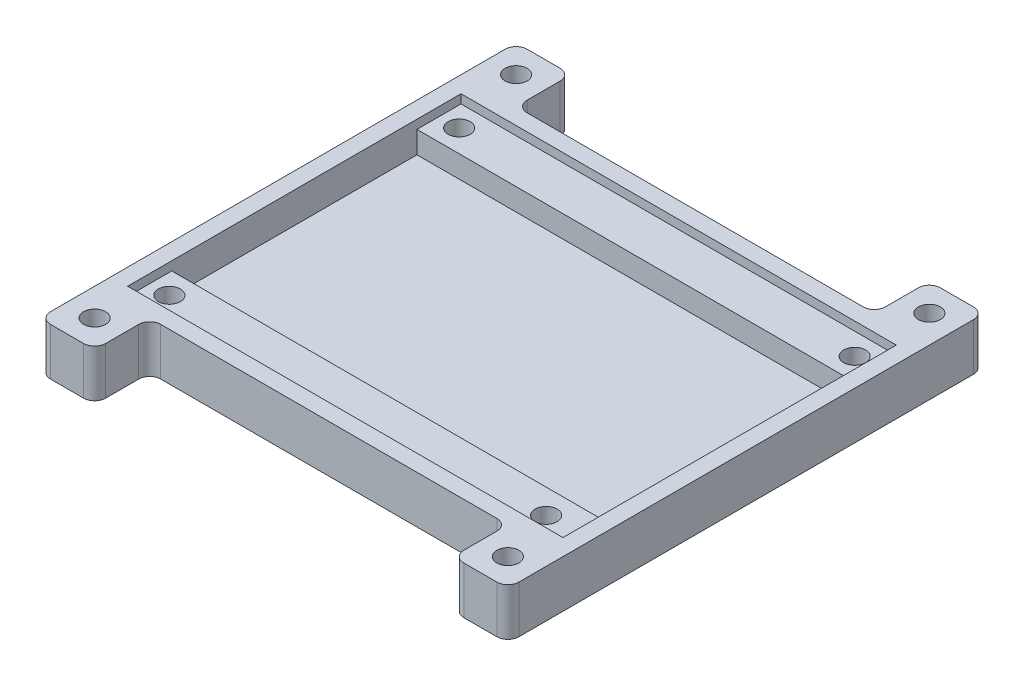
SolidWorks part; units mm, degrees
ref_plane "Front Plane" through (0, 0, 0) normal (0, 0, 1) x (1, 0, 0)
ref_plane "Top Plane" through (0, 0, 0) normal (0, 1, 0) x (1, 0, 0)
ref_plane "Right Plane" through (0, 0, 0) normal (1, 0, 0) x (0, 0, -1)
sketch "Sketch2" plane through (0, 0, 0) normal (0, 1, 0) x (1, 0, 0)
  line L1 (-42.5, -33.25) -> (42.5, -33.25)
  line L2 (-42.5, -33.25) -> (-42.5, 33.25)
  line L3 (-42.5, 33.25) -> (42.5, 33.25)
  line L4 (42.5, -33.25) -> (42.5, 33.25)
  line L5 (-42.5, -33.25) -> (42.5, 33.25) construction
  line L6 (-42.5, 33.25) -> (42.5, -33.25) construction
  point P0 (0, 0)
  dimension "D1" = 66.5
  dimension "D2" = 85
extrude "Boss-Extrude2" add sketch "Sketch2" along normal blind 3
sketch "Sketch3" plane through (0, 3, 0) normal (0, 1, 0) x (1, 0, 0)
  line L0 (-39.5, 30.25) -> (-39.5, -30.25)
  line L1 (-39.5, -30.25) -> (39.5, -30.25)
  line L2 (39.5, -30.25) -> (39.5, 30.25)
  line L3 (39.5, 30.25) -> (-39.5, 30.25)
  line L4 (42.5, -33.25) -> (42.5, 33.25)
  line L5 (42.5, 33.25) -> (-42.5, 33.25)
  line L6 (-42.5, 33.25) -> (-42.5, -33.25)
  line L7 (-42.5, -33.25) -> (42.5, -33.25)
  line L8 (42.5, -33.25) -> (42.5, 33.25)
  line L9 (42.5, 33.25) -> (-42.5, 33.25)
  line L10 (-42.5, 33.25) -> (-42.5, -33.25)
  line L11 (-42.5, -33.25) -> (42.5, -33.25)
  line L13 (-39.5, -30.25) -> (39.5, -30.25)
  line L14 (-39.5, -30.25) -> (-39.5, -22.25)
  line L15 (-39.5, -22.25) -> (39.5, -22.25)
  line L16 (39.5, -30.25) -> (39.5, -22.25)
  line L17 (-39.5, 30.25) -> (39.5, 30.25)
  line L18 (-39.5, 30.25) -> (-39.5, 22.25)
  line L19 (-39.5, 22.25) -> (39.5, 22.25)
  line L20 (39.5, 30.25) -> (39.5, 22.25)
  line M13 (42.5, -33.25) -> (42.5, 33.25)
  line M14 (42.5, 33.25) -> (-42.5, 33.25)
  line M15 (-42.5, 33.25) -> (-42.5, -33.25)
  line M16 (-42.5, -33.25) -> (42.5, -33.25)
  dimension "D3" = 8
  dimension "D4" = 8
  dimension "D1" = 0
  dimension "D2" = 3
extrude "Boss-Extrude3" add sketch "Sketch3" along normal blind 4 contours L3 L2 L1 L0 M16 M13 M14 M15 | L0 L19 L2 L3 | L15 L0 L1 L2
sketch "Sketch4" plane through (0, 7, 0) normal (0, 1, 0) x (1, 0, 0)
  line L0 (-35.89, -26.3) -> (-35.89, 26.3)
  line L1 (-39.5, 0) -> (39.5, 0)
  line L2 (-39.5, 22.25) -> (-39.5, -22.25) construction
  line L3 (39.5, -22.25) -> (39.5, 22.25) construction
  line L4 (-39.5, 22.25) -> (-39.5, -22.25) construction
  line L5 (35.89, -26.3) -> (35.89, 26.3)
  line L6 (39.5, -22.25) -> (39.5, 22.25) construction
  circle A0 centre (-35.89, 26.3) radius 2
  circle A1 centre (-35.89, -26.3) radius 2
  circle A2 centre (35.89, 26.3) radius 2
  circle A3 centre (32.89, -26.6968) radius 2
  point P9 (-35.89, 0)
  point P14 (35.89, 0)
  dimension "D3" = 4
  dimension "D1" = 52.6
  dimension "D2" = 3.61
  dimension "D4" = 3.61
extrude "Cut-Extrude1" cut sketch "Sketch4" against normal blind 4.5
sketch "Sketch5" plane through (0, 7, 0) normal (0, 1, 0) x (1, 0, 0)
  line L0 (42.5, -33.25) -> (42.5, 33.25) construction
  line L1 (-42.5, -33.25) -> (42.5, -33.25) construction
  line L2 (-42.5, 33.25) -> (-42.5, -33.25) construction
  line L3 (42.5, 33.25) -> (-42.5, 33.25) construction
  line L4 (42.5, -33.25) -> (42.5, 33.25)
  line L5 (-42.5, -33.25) -> (42.5, -33.25)
  line L6 (-42.5, 33.25) -> (-42.5, -33.25)
  line L7 (42.5, 33.25) -> (-42.5, 33.25)
  line L8 (-39.5, 30.25) -> (-39.5, -30.25)
  line L9 (-39.5, -30.25) -> (39.5, -30.25)
  line L10 (39.5, -30.25) -> (39.5, 30.25)
  line L11 (39.5, 30.25) -> (-39.5, 30.25)
  dimension "D1" = 3
extrude "Boss-Extrude4" add sketch "Sketch5" along normal blind 1.6
sketch "Sketch6" plane through (0, 0, 0) normal (0, -1, 0) x (1, 0, 0)
  line L1 (-42.5, -33.25) -> (-32.5, -33.25)
  line L2 (-42.5, -33.25) -> (-42.5, -43.25)
  line L3 (-42.5, -43.25) -> (-32.5, -43.25)
  line L4 (-32.5, -33.25) -> (-32.5, -43.25)
  line L5 (42.5, -33.25) -> (32.5, -33.25)
  line L6 (42.5, -33.25) -> (42.5, -43.25)
  line L7 (42.5, -43.25) -> (32.5, -43.25)
  line L8 (32.5, -33.25) -> (32.5, -43.25)
  line L9 (42.5, 33.25) -> (32.5, 33.25)
  line L10 (42.5, 33.25) -> (42.5, 43.25)
  line L11 (42.5, 43.25) -> (32.5, 43.25)
  line L12 (32.5, 33.25) -> (32.5, 43.25)
  line L13 (-42.5, 33.25) -> (-32.5, 33.25)
  line L14 (-42.5, 33.25) -> (-42.5, 43.25)
  line L15 (-42.5, 43.25) -> (-32.5, 43.25)
  line L16 (-32.5, 33.25) -> (-32.5, 43.25)
  dimension "D1" = 10
  dimension "D2" = 10
extrude "Boss-Extrude5" add sketch "Sketch6" along normal up to surface (8.6 mm away) from surface at -8.6 up to face at (0, 0, 0) starting at face at (0, 8.6, 0)
sketch "Sketch7" plane through (0, 8.6, 0) normal (0, 1, 0) x (1, 0, 0)
  line L0 (-32.5, 33.25) -> (-42.5, 43.25)
  line L1 (32.5, 33.25) -> (42.5, 43.25)
  line L2 (-42.5, -43.25) -> (-32.5, -33.25)
  line L3 (-32.5, -43.25) -> (-32.5, -33.25) construction
  line L4 (-32.5, -33.25) -> (32.5, -33.25) construction
  line L5 (32.5, -33.25) -> (42.5, -43.25)
  circle A0 centre (-37.5, -38.25) radius 2
  circle A1 centre (37.5, -38.25) radius 2
  circle A2 centre (37.5, 38.25) radius 2
  circle A3 centre (-37.5, 38.25) radius 2
  dimension "D1" = 4
  dimension "D2" = 4
  dimension "D3" = 4
  dimension "D4" = 4
extrude "Cut-Extrude2" cut sketch "Sketch7" against normal blind 4.5 contours L0 A3 | L0 A3 | L1 A2 | L1 A2 | L5 A1 | L5 A1 | L2 A0 | L2 A0
fillet "Fillet1" radius 2 12 edges at (-42.5, 4.3, 43.25) (-32.5, 4.3, 43.25) (-32.5, 4.3, 33.25) (32.5, 4.3, 33.25) (32.5, 4.3, 43.25) (42.5, 4.3, 43.25) (42.5, 4.3, -43.25) (32.5, 4.3, -33.25) (32.5, 4.3, -43.25) (-32.5, 4.3, -33.25) (-32.5, 4.3, -43.25) (-42.5, 4.3, -43.25)
